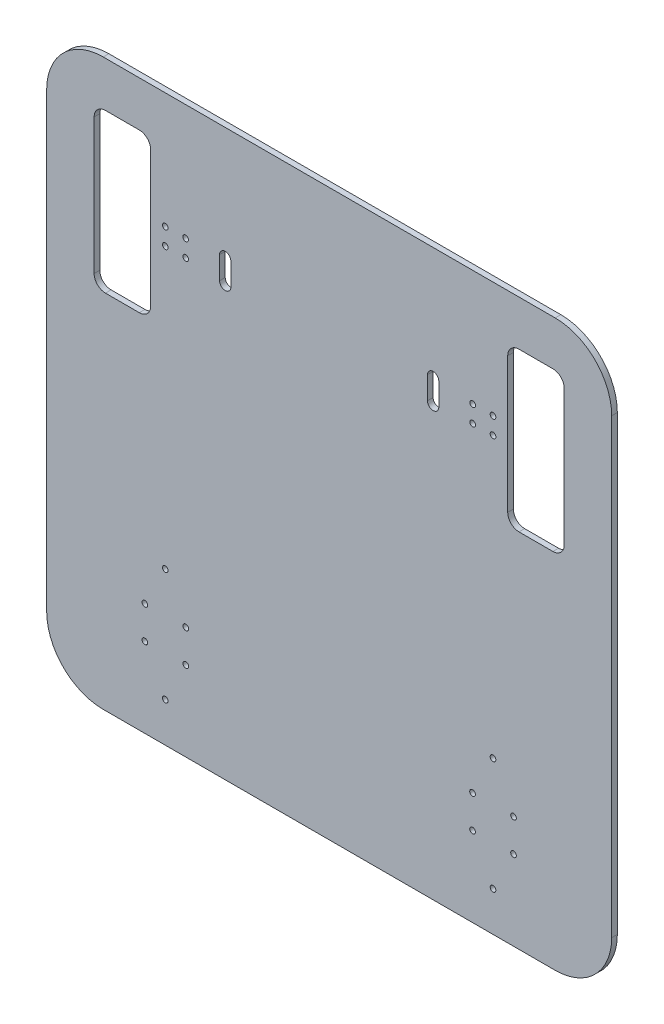
SolidWorks part; units mm, degrees
ref_plane "Front Plane" through (0, 0, 0) normal (0, 0, 1) x (1, 0, 0)
ref_plane "Top Plane" through (0, 0, 0) normal (0, 1, 0) x (1, 0, 0)
ref_plane "Right Plane" through (0, 0, 0) normal (1, 0, 0) x (0, 0, -1)
sketch "Sketch1" plane through (0, 0, 0) normal (0, 0, 1) x (1, 0, 0)
  line L0 (0, 0) -> (0, 250) construction
  line L4 (-145, 147.5) -> (-145, 132.5) construction
  line L5 (-127, 132.5) -> (-145, 132.5) construction
  line L6 (-127, 147.5) -> (-127, 132.5) construction
  line L7 (-127, 147.5) -> (-145, 147.5) construction
  line L8 (250, -250) -> (250, 250)
  line L9 (-250, -250) -> (250, -250)
  line L10 (-250, 250) -> (-250, -250)
  line L11 (250, 250) -> (-250, 250)
  line L17 (127, 147.5) -> (145, 147.5) construction
  line L18 (127, 147.5) -> (127, 132.5) construction
  line L19 (127, 132.5) -> (145, 132.5) construction
  line L20 (145, 147.5) -> (145, 132.5) construction
  line L21 (208, 210) -> (158, 210)
  line L22 (208, 210) -> (208, 70)
  line L23 (208, 70) -> (158, 70)
  line L24 (158, 210) -> (158, 70)
  line L25 (-158, 210) -> (-158, 70)
  line L26 (-208, 70) -> (-158, 70)
  line L27 (-208, 210) -> (-208, 70)
  line L28 (-208, 210) -> (-158, 210)
  line L29 (-145, 147.5) -> (-145, 132.5) construction
  line L30 (-155, 147.5) -> (-155, 132.5) construction
  line L31 (135, 147.5) -> (135, 132.5) construction
  line L32 (-135, 147.5) -> (-135, 132.5) construction
  line L33 (155, 147.5) -> (155, 132.5) construction
  circle A0 centre (127, 147.5) radius 2.5
  circle A1 centre (127, 132.5) radius 2.5
  circle A4 centre (145, 132.5) radius 2.5
  circle A5 centre (145, 147.5) radius 2.5
  circle A6 centre (-145, 147.5) radius 2.5
  circle A7 centre (-145, 132.5) radius 2.5
  circle A8 centre (-127, 132.5) radius 2.5
  circle A9 centre (-127, 147.5) radius 2.5
  point P3 (0, 250)
  point P4 (-250, 0)
  point P30 (127, 140)
  point P32 (158, 140)
  dimension "D8" = 5
  dimension "D11" = 18
  dimension "D3" = 500
  dimension "D4" = 10
  dimension "D5" = 10
  dimension "D7" = 15
  dimension "D9" = 81
  dimension "D10" = 270
  dimension "D12" = 50
  dimension "D13" = 140
  dimension "D16" = 40
  dimension "D2" = 500
extrude "Boss-Extrude1" add sketch "Sketch1" along normal blind 5
sketch "Sketch2" plane through (0, 0, 5) normal (0, 0, 1) x (1, 0, 0)
  line L0 (-145, 132.5) -> (-145, -250) construction
  line L1 (-250, -250) -> (250, -250) construction
  line L2 (0, 0) -> (0, -250) construction
  line L3 (-163.125, -179.4) -> (-126.875, -179.4) construction
  line L4 (-163.125, -179.4) -> (-163.125, -150.6) construction
  line L5 (-163.125, -150.6) -> (-126.875, -150.6) construction
  line L6 (-126.875, -179.4) -> (-126.875, -150.6) construction
  line L7 (-163.125, -179.4) -> (-126.875, -150.6) construction
  line L8 (-163.125, -150.6) -> (-126.875, -179.4) construction
  line L9 (163.125, -150.6) -> (126.875, -179.4) construction
  line L10 (163.125, -179.4) -> (126.875, -150.6) construction
  line L11 (126.875, -179.4) -> (126.875, -150.6) construction
  line L12 (163.125, -150.6) -> (126.875, -150.6) construction
  line L13 (163.125, -179.4) -> (163.125, -150.6) construction
  line L14 (163.125, -179.4) -> (126.875, -179.4) construction
  circle A0 centre (-145, 132.5) radius 2.5 construction
  circle A1 centre (-145, 132.5) radius 2.5
  circle A2 centre (-145, -165) radius 35 construction
  circle A3 centre (-163.125, -150.6) radius 2.5
  circle A4 centre (-126.875, -150.6) radius 2.5
  circle A5 centre (-126.875, -179.4) radius 2.5
  circle A6 centre (-163.125, -179.4) radius 2.5
  circle A7 centre (-145, -115) radius 2.5
  circle A8 centre (-145, -215) radius 2.5
  circle A9 centre (145, -165) radius 35 construction
  circle A10 centre (145, -215) radius 2.5
  circle A11 centre (145, -115) radius 2.5
  circle A12 centre (163.125, -179.4) radius 2.5
  circle A13 centre (126.875, -179.4) radius 2.5
  circle A14 centre (126.875, -150.6) radius 2.5
  circle A15 centre (163.125, -150.6) radius 2.5
  dimension "D1" = 70
  dimension "D5" = 5
  dimension "D6" = 50
  dimension "D2" = 50
  dimension "D3" = 28.8
  dimension "D4" = 36.25
  dimension "D7" = 50
extrude "Cut-Extrude1" cut sketch "Sketch2" against normal up to next (5 mm away)
fillet "Fillet1" radius 10 8 edges at (-208, 70, 2.5) (-158, 70, 2.5) (208, 70, 2.5) (158, 70, 2.5) (-208, 210, 2.5) (-158, 210, 2.5) (208, 210, 2.5) (158, 210, 2.5)
fillet "Fillet2" radius 50 4 edges at (-250, -250, 2.5) (250, -250, 2.5) (250, 250, 2.5) (-250, 250, 2.5)
sketch "Sketch3" plane through (0, 0, 5) normal (0, 0, 1) x (1, 0, 0)
  line L0 (0, 0) -> (0, 250) construction
  line L1 (-127, 130) -> (127, 130) construction
  line L2 (-127, 130) -> (-127, 150) construction
  line L3 (-127, 150) -> (127, 150) construction
  line L4 (127, 130) -> (127, 150) construction
  line L5 (-97, 130) -> (-87, 130)
  line L6 (-97, 130) -> (-97, 150)
  line L7 (-97, 150) -> (-87, 150)
  line L8 (-87, 130) -> (-87, 150)
  line L9 (200, 250) -> (-200, 250) construction
  line L10 (87, 130) -> (87, 150)
  line L11 (97, 130) -> (97, 150)
  circle A0 centre (-127, 132.5) radius 2.5 construction
  circle A1 centre (127, 147.5) radius 2.5 construction
  circle A2 centre (-127, 147.5) radius 2.5 construction
  arc A3 (-97, 130) -> (-87, 130) centre (-92, 130) ccw
  arc A4 (-97, 150) -> (-87, 150) centre (-92, 150) cw
  arc A5 (97, 150) -> (87, 150) centre (92, 150) ccw
  arc A6 (97, 130) -> (87, 130) centre (92, 130) cw
  point P19 (-127, 140)
  point P23 (-92, 130)
  point P24 (-87, 131.4765)
  dimension "D1" = 30
  dimension "D2" = 10
extrude "Cut-Extrude2" cut sketch "Sketch3" against normal through all contours L5 L8 L7 L6 | A4 L7 | L5 A3 | A6 L11 A5 L10
